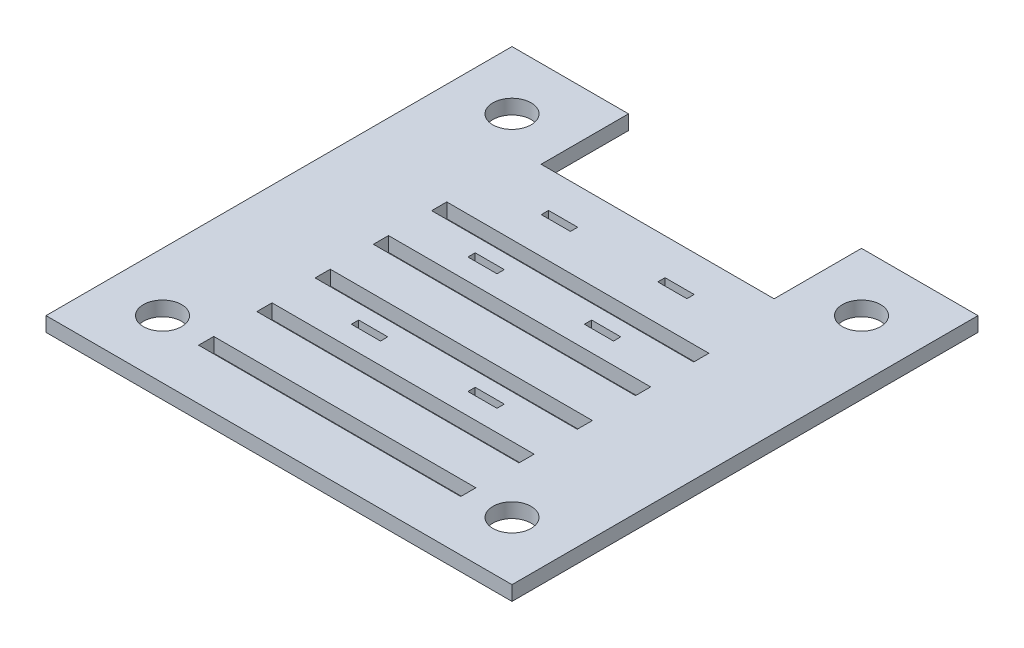
SolidWorks part; units mm, degrees
ref_plane "Front Plane" through (0, 0, 0) normal (0, 0, 1) x (1, 0, 0)
ref_plane "Top Plane" through (0, 0, 0) normal (0, 1, 0) x (1, 0, 0)
ref_plane "Right Plane" through (0, 0, 0) normal (1, 0, 0) x (0, 0, -1)
sketch "Sketch1" plane through (0, 0, 0) normal (0, 1, 0) x (1, 0, 0)
  line L1 (-101.6, 101.6) -> (101.6, 101.6)
  line L2 (-101.6, 101.6) -> (-101.6, -101.6)
  line L3 (-101.6, -101.6) -> (101.6, -101.6)
  line L4 (101.6, 101.6) -> (101.6, -101.6)
  line L5 (-101.6, 101.6) -> (101.6, -101.6) construction
  line L6 (-101.6, -101.6) -> (101.6, 101.6) construction
  point P0 (0, 0)
  dimension "D1" = 203.2
extrude "Boss-Extrude1" add sketch "Sketch1" along normal blind 6.35
sketch "Sketch3" plane through (0, 6.35, 0) normal (0, 1, 0) x (1, 0, 0)
  line L0 (-101.6, 101.6) -> (-101.6, -101.6) construction
  line L1 (101.6, 101.6) -> (-101.6, 101.6) construction
  line L2 (101.6, -101.6) -> (101.6, 101.6) construction
  line L3 (-101.6, -101.6) -> (101.6, -101.6) construction
  line L4 (0, 101.6) -> (0, -104.1597) construction
  line L5 (-50.8, 101.6) -> (50.8, 101.6)
  line L6 (-50.8, 101.6) -> (-50.8, 63.5)
  line L7 (-50.8, 63.5) -> (50.8, 63.5)
  line L8 (50.8, 101.6) -> (50.8, 63.5)
  line L9 (-50.8, 101.6) -> (50.8, 63.5) construction
  line L10 (-50.8, 63.5) -> (50.8, 101.6) construction
  circle A0 centre (-76.2, 76.2) radius 8.3344
  circle A1 centre (76.2, 76.2) radius 8.3344
  circle A2 centre (-76.2, -76.2) radius 8.3344
  circle A3 centre (76.2, -76.2) radius 8.3344
  point P16 (0, 82.55)
  dimension "D3" = 16.6687
  dimension "D1" = 25.4
  dimension "D2" = 25.4
  dimension "D4" = 25.4
  dimension "D5" = 25.4
  dimension "D6" = 38.1
  dimension "D7" = 101.6
extrude "Cut-Extrude1" cut sketch "Sketch3" against normal through all
sketch "Sketch4" plane through (0, 6.35, 0) normal (0, 1, 0) x (1, 0, 0)
  line L0 (-57.15, -54.102) -> (57.15, -54.102)
  line L1 (-50.8, 101.6) -> (-101.6, 101.6) construction
  line L2 (-57.15, 28.702) -> (57.15, 28.702)
  line L3 (-57.15, 28.702) -> (-57.15, 22.098)
  line L4 (-57.15, 22.098) -> (57.15, 22.098)
  line L5 (57.15, 28.702) -> (57.15, 22.098)
  line L6 (-57.15, 28.702) -> (57.15, 22.098) construction
  line L7 (57.15, -47.498) -> (57.15, -54.102)
  line L8 (-57.15, -47.498) -> (57.15, -47.498)
  line L9 (-57.15, -47.498) -> (-57.15, -54.102)
  line L10 (-57.15, -79.502) -> (57.15, -79.502)
  line L11 (-57.15, 22.098) -> (57.15, 28.702) construction
  line L12 (0, 101.6) -> (0, -104.1597) construction
  line L13 (57.15, -72.898) -> (57.15, -79.502)
  line L14 (-57.15, -72.898) -> (57.15, -72.898)
  line L15 (-57.15, -3.302) -> (57.15, -3.302)
  line L16 (57.15, 3.302) -> (57.15, -3.302)
  line L17 (-57.15, 3.302) -> (57.15, 3.302)
  line L18 (-57.15, 3.302) -> (-57.15, -3.302)
  line L19 (-57.15, -28.702) -> (57.15, -28.702)
  line L20 (57.15, -22.098) -> (57.15, -28.702)
  line L21 (-57.15, -22.098) -> (57.15, -22.098)
  line L22 (-57.15, -22.098) -> (-57.15, -28.702)
  line L23 (-57.15, -72.898) -> (-57.15, -79.502)
  point P0 (0, 25.4)
  dimension "D1" = 76.2
  dimension "D2" = 6.604
  dimension "D3" = 114.3
  dimension "D4" = 5
extrude "Cut-Extrude2" cut sketch "Sketch4" against normal through all
sketch "Sketch5" plane through (0, 6.35, 0) normal (0, 1, 0) x (1, 0, 0)
  line L0 (0, 101.6) -> (0, -104.1597) construction
  line L1 (-31.75, 47.6885) -> (-19.05, 47.6885)
  line L2 (-31.75, 47.6885) -> (-31.75, 44.5135)
  line L3 (-31.75, 44.5135) -> (-19.05, 44.5135)
  line L4 (-19.05, 47.6885) -> (-19.05, 44.5135)
  line L5 (-31.75, 47.6885) -> (-19.05, 44.5135) construction
  line L6 (-31.75, 44.5135) -> (-19.05, 47.6885) construction
  line L7 (-50.8, 63.5) -> (50.8, 63.5) construction
  line L8 (19.05, 47.6885) -> (31.75, 47.6885)
  line L9 (19.05, 47.6885) -> (19.05, 44.5135)
  line L10 (19.05, 44.5135) -> (31.75, 44.5135)
  line L11 (31.75, 47.6885) -> (31.75, 44.5135)
  line L12 (19.05, 47.6885) -> (31.75, 44.5135) construction
  line L13 (19.05, 44.5135) -> (31.75, 47.6885) construction
  line L14 (-31.75, 15.6885) -> (-19.05, 15.6885)
  line L15 (-31.75, 15.6885) -> (-31.75, 12.5135)
  line L16 (-31.75, 12.5135) -> (-19.05, 12.5135)
  line L17 (-19.05, 15.6885) -> (-19.05, 12.5135)
  line L18 (19.05, 15.6885) -> (31.75, 15.6885)
  line L19 (19.05, 15.6885) -> (19.05, 12.5135)
  line L20 (19.05, 12.5135) -> (31.75, 12.5135)
  line L21 (31.75, 15.6885) -> (31.75, 12.5135)
  line L22 (-31.75, 15.6885) -> (-19.05, 12.5135) construction
  line L23 (-31.75, 12.5135) -> (-19.05, 15.6885) construction
  line L24 (19.05, 15.6885) -> (31.75, 12.5135) construction
  line L25 (19.05, 12.5135) -> (31.75, 15.6885) construction
  line L26 (-31.75, -35.1115) -> (-19.05, -35.1115)
  line L27 (-31.75, -35.1115) -> (-31.75, -38.2865)
  line L28 (-31.75, -38.2865) -> (-19.05, -38.2865)
  line L29 (-19.05, -35.1115) -> (-19.05, -38.2865)
  line L30 (19.05, -35.1115) -> (31.75, -35.1115)
  line L31 (19.05, -35.1115) -> (19.05, -38.2865)
  line L32 (19.05, -38.2865) -> (31.75, -38.2865)
  line L33 (31.75, -35.1115) -> (31.75, -38.2865)
  line L34 (-31.75, -35.1115) -> (-19.05, -38.2865) construction
  line L35 (-31.75, -38.2865) -> (-19.05, -35.1115) construction
  line L36 (19.05, -35.1115) -> (31.75, -38.2865) construction
  line L37 (19.05, -38.2865) -> (31.75, -35.1115) construction
  point P0 (-25.4, 46.101)
  point P10 (25.4, 46.101)
  point P15 (-25.4, 14.101)
  point P20 (25.4, 14.101)
  point P26 (-25.4, -36.699)
  point P31 (25.4, -36.699)
  dimension "D1" = 12.7
  dimension "D2" = 3.175
  dimension "D3" = 25.4
  dimension "D4" = 17.399
  dimension "D5" = 2
  dimension "D6" = 2
  dimension "D7" = 2
extrude "Cut-Extrude3" cut sketch "Sketch5" against normal through all
